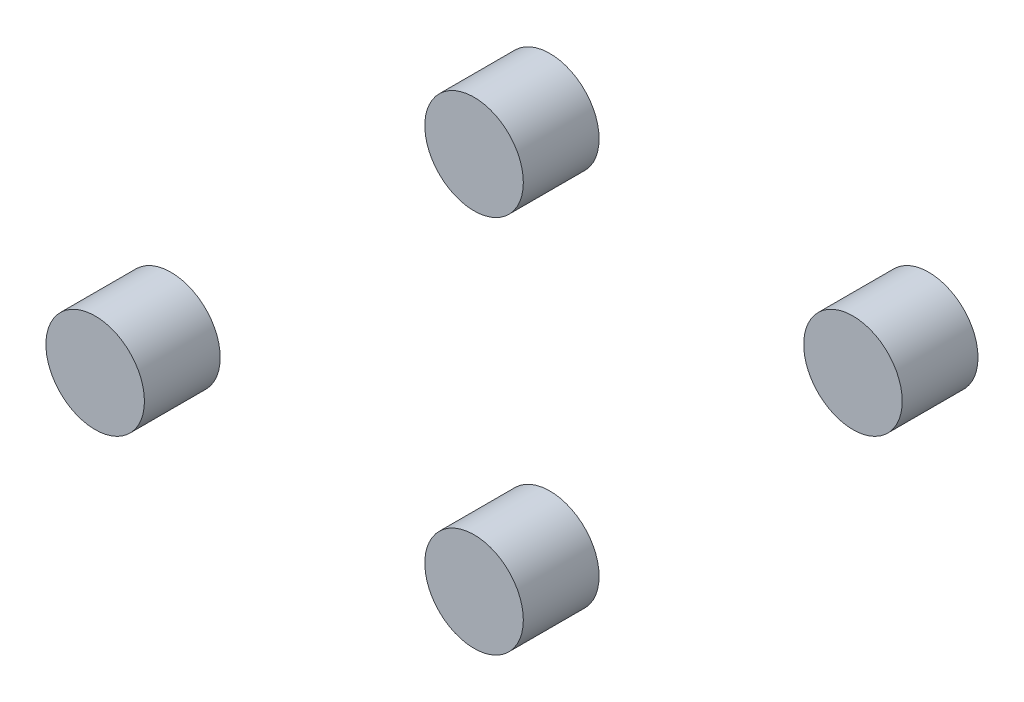
SolidWorks part; units mm, degrees
ref_plane "Front" through (0, 0, 0) normal (0, 0, 1) x (1, 0, 0)
ref_plane "Top" through (0, 0, 0) normal (0, 1, 0) x (1, 0, 0)
ref_plane "Right" through (0, 0, 0) normal (1, 0, 0) x (0, 0, -1)
sketch "Sketch1" plane through (0, 0, 0) normal (0, 0, 1) x (1, 0, 0)
  line L0 (55, 0) -> (-55, 0) construction
  circle A0 centre (0, 0) radius 49.53
  circle A1 centre (381, 0) radius 49.53
  dimension "D1" = 99.06
  dimension "D2" = 381
extrude "Boss-Extrude1" add sketch "Sketch1" against normal blind 76.2 from offset 228.6
mirror "Mirror3" about plane through (0, 0, 0) normal (0, 0, 1) of bodies 101 102
